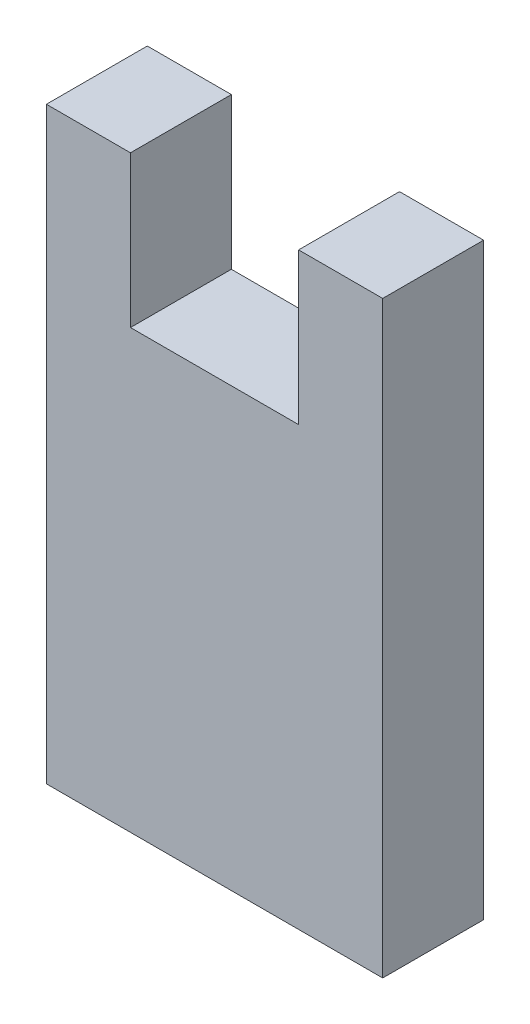
SolidWorks part; units mm, degrees
material "ABS"
ref_plane "Płaszczyzna przednia" through (0, 0, 0) normal (0, 0, 1) x (1, 0, 0)
ref_plane "Płaszczyzna górna" through (0, 0, 0) normal (0, 1, 0) x (1, 0, 0)
ref_plane "Płaszczyzna prawa" through (0, 0, 0) normal (1, 0, 0) x (0, 0, -1)
sketch "Szkic1" plane through (0, 0, 0) normal (0, 0, 1) x (1, 0, 0)
  line L1 (-20, -35) -> (20, -35)
  line L2 (-20, -35) -> (-20, 35)
  line L3 (-20, 35) -> (20, 35)
  line L4 (20, -35) -> (20, 35)
  line L5 (-20, -35) -> (20, 35) construction
  line L6 (-20, 35) -> (20, -35) construction
  point P0 (0, 0)
  dimension "D1" = 40
  dimension "D2" = 70
extrude "Dodanie-wyciągnięcie1" add sketch "Szkic1" along normal blind 12
sketch "Szkic2" plane through (0, 0, 12) normal (0, 0, 1) x (1, 0, 0)
  line L0 (20, 35) -> (-20, 35) construction
  line L1 (-10, 35) -> (10, 35)
  line L2 (-10, 35) -> (-10, 17)
  line L3 (-10, 17) -> (10, 17)
  line L4 (10, 35) -> (10, 17)
  line L5 (-20, 35) -> (-20, -35) construction
  dimension "D1" = 20
  dimension "D2" = 10
  dimension "D3" = 18
extrude "Wytnij-wyciągnięcie1" cut sketch "Szkic2" against normal through all
